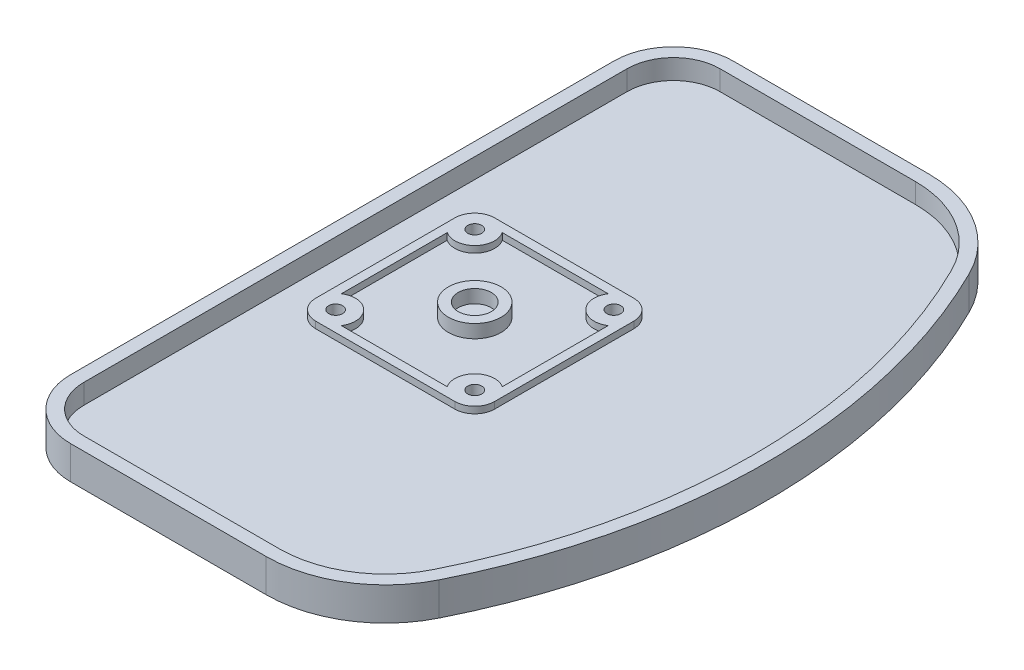
SolidWorks part; units mm, degrees
material "ABS"
ref_plane "Front" through (0, 0, 0) normal (0, 0, 1) x (1, 0, 0)
ref_plane "Top" through (0, 0, 0) normal (0, 1, 0) x (1, 0, 0)
ref_plane "Right" through (0, 0, 0) normal (1, 0, 0) x (0, 0, -1)
sketch "ｽｹｯﾁ1" plane through (0, 0, 0) normal (0, 1, 0) x (1, 0, 0)
  line L0 (-20, 0) -> (44, 0) construction
  line L1 (-20, 50) -> (28.8331, 50)
  line L2 (-20, 50) -> (-20, -50)
  line L3 (-20, -50) -> (28.8331, -50)
  line L5 (-20, 50) -> (22.854, -57.135) construction
  line L6 (-20, -50) -> (29.8928, 74.732) construction
  arc A0 (28.8331, -50) -> (28.8331, 50) centre (-46, 0) ccw
  point P0 (0, 0)
  dimension "D2" = 180
  dimension "D3" = 0
  dimension "D1" = 100
  dimension "D4" = 64
  dimension "D5" = 0
  dimension "D6" = 20
extrude "ﾎﾞｽ - 押し出し1" add sketch "ｽｹｯﾁ1" along normal blind 5
fillet "ﾌｨﾚｯﾄ1" radius 9 2 edges at (-20, 2.5, -50) (-20, 2.5, 50)
fillet "ﾌｨﾚｯﾄ2" radius 18 2 edges at (28.8331, 2.5, -50) (28.8331, 2.5, 50)
shell "ｼｪﾙ1" thickness 2
sketch "ｽｹｯﾁ2" plane through (0, 2, 0) normal (0, 1, 0) x (1, 0, 0)
  line L1 (-13.5, 13.5) -> (13.5, 13.5)
  line L2 (-13.5, 13.5) -> (-13.5, -13.5)
  line L3 (-13.5, -13.5) -> (13.5, -13.5)
  line L4 (13.5, 13.5) -> (13.5, -13.5)
  line L5 (-13.5, 13.5) -> (13.5, -13.5) construction
  line L6 (-13.5, -13.5) -> (13.5, 13.5) construction
  point P0 (0, 0)
  dimension "D1" = 27
  dimension "D2" = 27
extrude "ﾎﾞｽ - 押し出し2" add sketch "ｽｹｯﾁ2" along normal blind 1
sketch "ｽｹｯﾁ3" plane through (0, 3, 0) normal (0, 1, 0) x (1, 0, 0)
  circle A0 centre (0, 0) radius 3.975
  dimension "D1" = 7.95
extrude "ﾎﾞｽ - 押し出し3" add sketch "ｽｹｯﾁ3" along normal blind 1
fillet "ﾌｨﾚｯﾄ3" radius 3 4 edges at (-13.5, 2.5, -13.5) (13.5, 2.5, -13.5) (13.5, 2.5, 13.5) (-13.5, 2.5, 13.5)
hole_wizard "M2 なべ頭ねじ用座ぐり穴1" positions "ｽｹｯﾁ4" profile "ｽｹｯﾁ5" counterbore size "M2" standard "ISO" end condition up to next
sketch "ｽｹｯﾁ4" plane through (0, 0, 0) normal (0, -1, 0) x (-1, 0, 0)
  point P0 (10.5, 10.5)
  dimension "D1" = 10.5
  dimension "D2" = 10.5
sketch "ｽｹｯﾁ5" plane through (-10.5, 0, -10.5) normal (1, 0, 0) x (0, 0, -1)
  line L0 (0, 0) -> (0, 3)
  line L1 (0, 3) -> (1.05, 3)
  line L3 (1.05, 3) -> (1.05, 1)
  line L4 (1.05, 1) -> (1.9, 1)
  line L5 (1.9, 1) -> (1.9, 0)
  line L7 (1.9, 0) -> (0, 0)
  line L11 (0, -6.35) -> (0, 107.95) construction
  dimension "通し穴の直径" = 2.1
  dimension "通し穴の深さ" = 3
  dimension "座ぐり穴の直径" = 3.8
  dimension "座ぐり穴の深さ" = 1
pattern_circular "円形ﾊﾟﾀｰﾝ1" count 4 over 360 about axis through (0, 0, 0) along (0, 1, 0) of "M2 なべ頭ねじ用座ぐり穴1"
sketch "ｽｹｯﾁ6" plane through (0, 3, 0) normal (0, 1, 0) x (1, 0, 0)
  line L0 (-13.5, 10.5) -> (-13.5, -10.5) construction
  line L1 (12.15, -12.15) -> (-12.15, -12.15)
  line L2 (12.15, -12.15) -> (12.15, 12.15)
  line L3 (12.15, 12.15) -> (-12.15, 12.15)
  line L4 (-12.15, -12.15) -> (-12.15, 12.15)
  line L5 (12.15, -12.15) -> (-12.15, 12.15) construction
  line L6 (12.15, 12.15) -> (-12.15, -12.15) construction
  circle A0 centre (-10.5, 10.5) radius 3
  circle A1 centre (10.5, 10.5) radius 3
  circle A2 centre (-10.5, -10.5) radius 3
  circle A3 centre (10.5, -10.5) radius 3
  circle A4 centre (0, 0) radius 3.975
  point P12 (0, 0)
  circle M7 centre (0, 0) radius 3.975
  dimension "D1" = 6
  dimension "D2" = 6
  dimension "D3" = 6
  dimension "D4" = 6
  dimension "D6" = 7.95
  dimension "D5" = 1.35
extrude "ｶｯﾄ - 押し出し1" cut sketch "ｽｹｯﾁ6" against normal up to surface (1 mm away) contours A3 L2 A1 L3 A0 L4 A2 L1 M7
sketch "ｽｹｯﾁ7" plane through (0, 4, 0) normal (0, 1, 0) x (1, 0, 0)
  circle A0 centre (0, 0) radius 2.5
  dimension "D1" = 5
extrude "ｶｯﾄ - 押し出し2" cut sketch "ｽｹｯﾁ7" against normal up to surface (2 mm away) up to face at (0, 2, 3.975)
